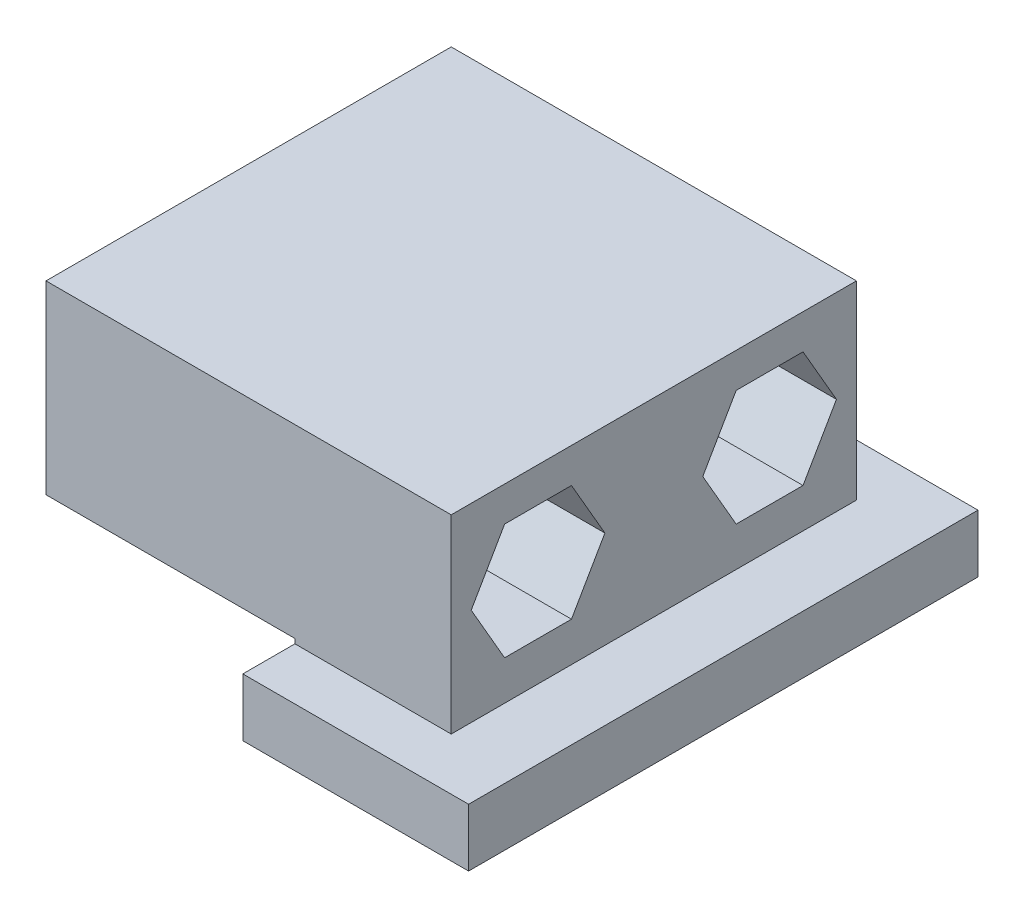
SolidWorks part; units mm, degrees
material "PLA"
ref_plane "前视基准面" through (0, 0, 0) normal (0, 0, 1) x (1, 0, 0)
ref_plane "上视基准面" through (0, 0, 0) normal (0, 1, 0) x (1, 0, 0)
ref_plane "右视基准面" through (0, 0, 0) normal (1, 0, 0) x (0, 0, -1)
sketch "草图1" plane through (0, 0, 0) normal (0, 1, 0) x (1, 0, 0)
  line L1 (-8.75, -8.75) -> (8.75, -8.75)
  line L2 (-8.75, -8.75) -> (-8.75, 8.75)
  line L3 (-8.75, 8.75) -> (8.75, 8.75)
  line L4 (8.75, -8.75) -> (8.75, 8.75)
  line L5 (0, 8.75) -> (0, -8.75) construction
  line L6 (-8.75, 0) -> (8.75, 0) construction
  point P0 (0, 0)
  dimension "D1" = 17.5
extrude "凸台-拉伸1" add sketch "草图1" along normal blind 8
sketch "草图2" plane through (8.75, 0, 0) normal (1, 0, 0) x (0, 0, -1)
  line L0 (8.75, 4) -> (-8.75, 4) construction
  line L1 (8.75, 8) -> (8.75, 0) construction
  line L2 (-8.75, 8) -> (-8.75, 0) construction
  line L3 (0, 0) -> (0, 8) construction
  line L4 (-8.75, 8) -> (8.75, 8) construction
  circle A0 centre (5, 4) radius 1.35
  circle A1 centre (-5, 4) radius 1.35
  dimension "D1" = 2.7
  dimension "D2" = 10
extrude "切除-拉伸1" cut sketch "草图2" against normal through all
sketch "草图3" plane through (8.75, 0, 0) normal (1, 0, 0) x (0, 0, -1)
  line L0 (0, 0) -> (0, 8) construction
  line L1 (7.8868, 4) -> (6.4434, 6.5)
  line L2 (6.4434, 6.5) -> (3.5566, 6.5)
  line L3 (3.5566, 6.5) -> (2.1132, 4)
  line L4 (2.1132, 4) -> (3.5566, 1.5)
  line L5 (3.5566, 1.5) -> (6.4434, 1.5)
  line L6 (6.4434, 1.5) -> (7.8868, 4)
  line L7 (-8.75, 8) -> (8.75, 8) construction
  line L8 (-6.4434, 1.5) -> (-7.8868, 4)
  line L9 (-3.5566, 1.5) -> (-6.4434, 1.5)
  line L10 (-2.1132, 4) -> (-3.5566, 1.5)
  line L11 (-3.5566, 6.5) -> (-2.1132, 4)
  line L12 (-6.4434, 6.5) -> (-3.5566, 6.5)
  line L13 (-7.8868, 4) -> (-6.4434, 6.5)
  circle A0 centre (5, 4) radius 2.5 construction
  dimension "D1" = 5
extrude "切除-拉伸2" cut sketch "草图3" against normal blind 4
sketch "草图5" plane through (0, 0, 0) normal (0, -1, 0) x (1, 0, 0)
  line L1 (8.75, -8.75) -> (2, -8.75)
  line L2 (8.75, -8.75) -> (8.75, 8.75)
  line L3 (8.75, 8.75) -> (2, 8.75)
  line L4 (2, -8.75) -> (2, 8.75)
  line L5 (5.375, 8.75) -> (5.375, -8.75) construction
  line L6 (8.75, 0) -> (0, 0) construction
  line L7 (-8.75, 8.75) -> (8.75, 8.75) construction
  line L8 (8.75, 8.75) -> (8.75, -8.75) construction
  line L9 (8.75, -8.75) -> (-8.75, -8.75) construction
  point P236 (5.375, 0)
  dimension "D1" = 2
extrude "凸台-拉伸3" add sketch "草图5" along normal blind 0.2
sketch "草图6" plane through (0, -0.2, 0) normal (0, -1, 0) x (1, 0, 0)
  line L1 (11.75, -11) -> (2, -11)
  line L2 (11.75, -11) -> (11.75, 11)
  line L3 (11.75, 11) -> (2, 11)
  line L4 (2, -11) -> (2, 11)
  line L5 (6.875, 11) -> (6.875, -11) construction
  line L6 (11.75, 0) -> (2, 0) construction
  line L8 (2, -8.75) -> (2, 8.75) construction
  line L9 (8.75, 8.75) -> (8.75, -8.75) construction
  point P152 (6.875, 0)
  dimension "D1" = 22
  dimension "D2" = 3
extrude "凸台-拉伸4" add sketch "草图6" along normal blind 2.5
